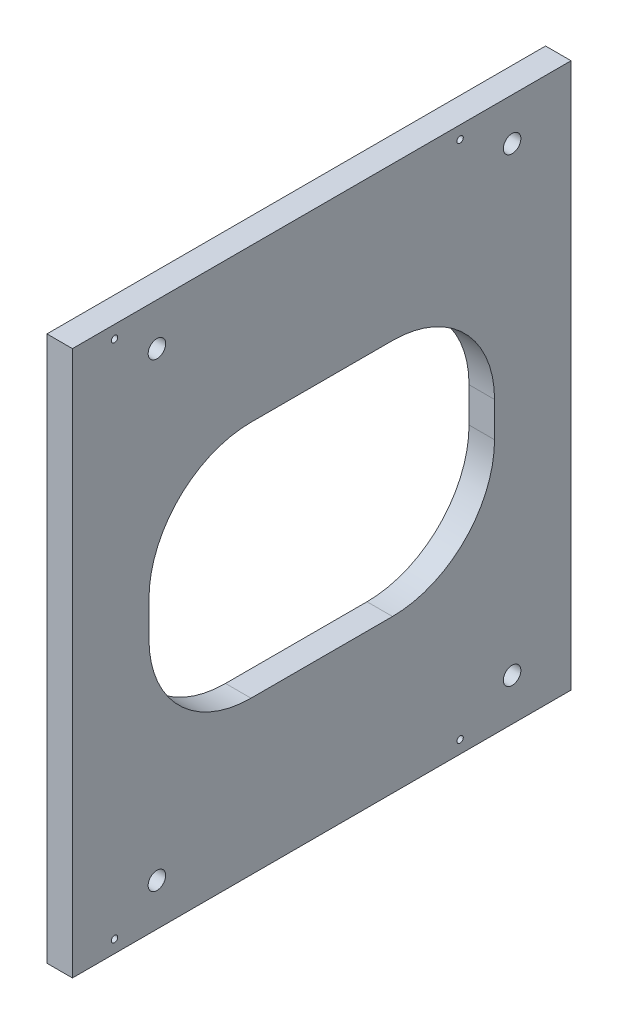
SolidWorks part; units mm, degrees
material "Beech"
ref_plane "Front Plane" through (0, 0, 0) normal (0, 0, 1) x (1, 0, 0)
ref_plane "Top Plane" through (0, 0, 0) normal (0, 1, 0) x (1, 0, 0)
ref_plane "Right Plane" through (0, 0, 0) normal (1, 0, 0) x (0, 0, -1)
sketch "Sketch1" plane through (0, 0, 0) normal (0, 0, 1) x (1, 0, 0)
  line L0 (-234.753, -188.5238) -> (-91.9973, -188.5238) construction
  line L1 (-234.753, 82.8417) -> (-222.053, 82.8417)
  line L2 (-234.753, 82.8417) -> (-234.753, -188.5238)
  line L3 (-234.753, -188.5238) -> (-222.053, -188.5238)
  line L4 (-222.053, 82.8417) -> (-222.053, -188.5238)
  dimension "D1" = 12.7
extrude "Boss-Extrude1" add sketch "Sketch1" along normal offset from surface (248.25 mm away) 19.05
sketch "Sketch2" plane through (-234.753, 0, 0) normal (-1, 0, 0) x (0, 0, 1)
  line L0 (124.125, 82.8417) -> (124.125, -52.841) construction
  line L1 (248.25, 82.8417) -> (0, 82.8417) construction
  line L2 (124.125, -52.841) -> (248.25, -52.841) construction
  line L3 (248.25, 82.8417) -> (248.25, -188.5238) construction
  line L5 (38.1, -112.3238) -> (210.15, -112.3238)
  line L6 (38.1, -112.3238) -> (38.1, 6.6417)
  line L7 (38.1, 6.6417) -> (210.15, 6.6417)
  line L8 (210.15, -112.3238) -> (210.15, 6.6417)
  line L9 (38.1, -112.3238) -> (210.15, 6.6417) construction
  line L10 (38.1, 6.6417) -> (210.15, -112.3238) construction
  dimension "D1" = 38.1
  dimension "D2" = 76.2
extrude "Cut-Extrude1" cut sketch "Sketch2" against normal through all
fillet "Fillet1" radius 50.8 4 edges at (-228.403, 6.6417, 38.1) (-228.403, -112.3238, 38.1) (-228.403, -112.3238, 210.15) (-228.403, 6.6417, 210.15)
hole_wizard "Hole1" positions "Sketch3" profile "Sketch4" legacy
sketch "Sketch3" plane through (181.0394, -52.975, -12.7) normal (0, 0, -1) x (0, -1, 0)
  line L0 (-129.4667, 415.7924) -> (-129.4667, 273.0368) construction
  line L5 (-135.8167, 409.4424) -> (135.5488, 409.4424) construction
  line L10 (-135.8167, 279.3868) -> (135.5488, 279.3868) construction
  line L11 (-0.134, 409.4424) -> (-0.134, 279.3868) construction
  point P22 (-129.4667, 384.0424)
  point P24 (-129.4667, 304.7868)
  point P26 (-110.4167, 409.4424)
  point P30 (-0.134, 409.4424)
  point P50 (110.1488, 409.4424)
  point P51 (129.1988, 304.7868)
  point P52 (129.1988, 384.0424)
sketch "Sketch4" plane through (-203.003, -182.1738, -12.7) normal (1, 0, 0) x (0, 1, 0)
  line L0 (0, 0) -> (0, 32.7039)
  line L1 (0, 32.7039) -> (1.5875, 31.75)
  line L2 (1.5875, 31.75) -> (1.5875, 4.0177)
  line L3 (1.5875, 4.0177) -> (5.08, 0)
  line L4 (5.08, 0) -> (0, 0)
  line L5 (0, -14.3089) -> (0, 102.4216) construction
  line L6 (0, 32.7039) -> (-1.5875, 31.75) construction
  line L7 (-1.5875, 4.0177) -> (-5.08, 0) construction
  dimension "Diameter" = 3.175
  dimension "Depth" = 31.75
  dimension "C-Sink Diameter" = 10.16
  dimension "C-Sink Angle" = 82
  dimension "Drill Angle" = 118
hole_wizard "Hole2" positions "Sketch5" profile "Sketch6" legacy
sketch "Sketch5" plane through (-234.753, -52.975, -1073.3642) normal (-1, 0, 0) x (0, -1, 0)
  line L3 (-0.134, 1338.7628) -> (-0.134, 1090.5128) construction
  point P1 (-129.4667, 1300.6628)
  point P3 (-129.4667, 1128.6128)
  point P15 (129.1988, 1128.6128)
  point P16 (129.1988, 1300.6628)
sketch "Sketch6" plane through (-234.753, 76.4917, 227.2986) normal (0, 1, 0) x (0, 0, 1)
  line L0 (0, 0) -> (0, 32.7039)
  line L1 (0, 32.7039) -> (1.5875, 31.75)
  line L2 (1.5875, 31.75) -> (1.5875, 4.0177)
  line L3 (1.5875, 4.0177) -> (5.08, 0)
  line L4 (5.08, 0) -> (0, 0)
  line L5 (0, -14.3089) -> (0, 102.4216) construction
  line L6 (0, 32.7039) -> (-1.5875, 31.75) construction
  line L7 (-1.5875, 4.0177) -> (-5.08, 0) construction
  dimension "Diameter" = 3.175
  dimension "Depth" = 31.75
  dimension "C-Sink Diameter" = 10.16
  dimension "C-Sink Angle" = 82
  dimension "Drill Angle" = 118
hole_wizard "Hole3" positions "Sketch7" profile "Sketch8" legacy
sketch "Sketch7" plane through (-222.053, -52.975, -1073.3642) normal (1, 0, 0) x (0, 1, 0)
  line L0 (100.6, 1338.7628) -> (100.6, 1090.5128) construction
  line L6 (0.134, 1338.7628) -> (0.134, 1090.5128) construction
  point P12 (100.6, 1313.3628)
  point P14 (100.6, 1115.9128)
  point P16 (100.6, 1214.6378)
  point P22 (-100.332, 1214.6378)
  point P23 (-100.332, 1115.9128)
  point P24 (-100.332, 1313.3628)
sketch "Sketch8" plane through (-222.053, -153.307, 239.9986) normal (0, 1, 0) x (0, 0, -1)
  line L0 (0, 0) -> (0, 32.7039)
  line L1 (0, 32.7039) -> (1.5875, 31.75)
  line L2 (1.5875, 31.75) -> (1.5875, 4.0177)
  line L3 (1.5875, 4.0177) -> (5.08, 0)
  line L4 (5.08, 0) -> (0, 0)
  line L5 (0, -14.3089) -> (0, 102.4216) construction
  line L6 (0, 32.7039) -> (-1.5875, 31.75) construction
  line L7 (-1.5875, 4.0177) -> (-5.08, 0) construction
  dimension "Diameter" = 3.175
  dimension "Depth" = 31.75
  dimension "C-Sink Diameter" = 10.16
  dimension "C-Sink Angle" = 82
  dimension "Drill Angle" = 118
hole_wizard "5/16 Clearance Hole1" positions "Sketch9" profile "Sketch10" hole size "5/16" standard "ANSI Inch" end condition through all
sketch "Sketch9" plane through (-234.753, 0, 0) normal (-1, 0, 0) x (0, 0, 1)
  line L0 (248.25, -52.841) -> (0, -52.841) construction
  line L1 (248.25, 82.8417) -> (248.25, -188.5238) construction
  line L2 (0, 82.8417) -> (0, -188.5238) construction
  line L4 (206.1876, 82.8417) -> (206.1876, -52.841) construction
  line L6 (29.3624, 82.8417) -> (29.3624, -52.841) construction
  line L8 (248.25, 82.8417) -> (0, 82.8417) construction
  point P24 (206.1876, 61.7855)
  point P26 (29.3624, 61.7855)
  point P31 (29.3624, -167.4675)
  point P32 (206.1876, -167.4675)
  dimension "D1" = 42.0624
  dimension "D2" = 29.3624
  dimension "D3" = 21.0562
sketch "Sketch10" plane through (-234.753, -167.4675, 206.1876) normal (0, 1, 0) x (0, 0, 1)
  line L0 (0, 0) -> (0, 12.7)
  line L1 (0, 12.7) -> (4.365, 12.7)
  line L2 (4.365, 12.7) -> (4.365, 0)
  line L5 (4.365, 0) -> (0, 0)
  line L11 (0, -6.35) -> (0, 107.95) construction
  dimension "Thru Hole Dia." = 8.73
  dimension "Thru Hole Depth" = 12.7
